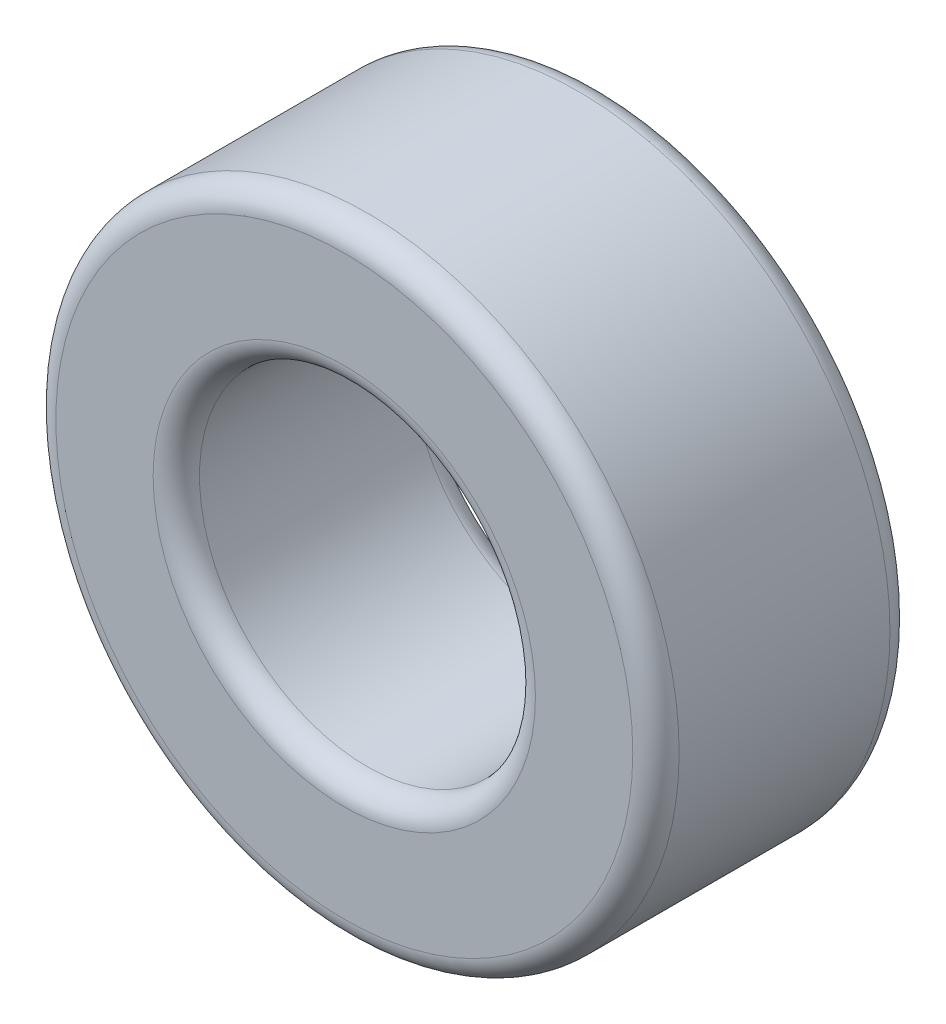
SolidWorks part; units mm, degrees
material "Ferro fundido cinza (SN)"
ref_plane "Plano frontal" through (0, 0, 0) normal (0, 0, 1) x (1, 0, 0)
ref_plane "Plano superior" through (0, 0, 0) normal (0, 1, 0) x (1, 0, 0)
ref_plane "Plano direito" through (0, 0, 0) normal (1, 0, 0) x (0, 0, -1)
sketch "Esboço1" plane through (0, 0, 0) normal (0, 0, 1) x (1, 0, 0)
  circle A0 centre (0, 0) radius 13.45
  circle A1 centre (0, 0) radius 7.25
  dimension "D1" = 26.9
  dimension "D2" = 14.5
extrude "Ressalto-extrusão1" add sketch "Esboço1" along normal blind 11.1
fillet "Filete1" radius 1 4 edges at (13.45, 0, 0) (13.45, 0, 11.1) (7.25, 0, 0) (7.25, 0, 11.1)
